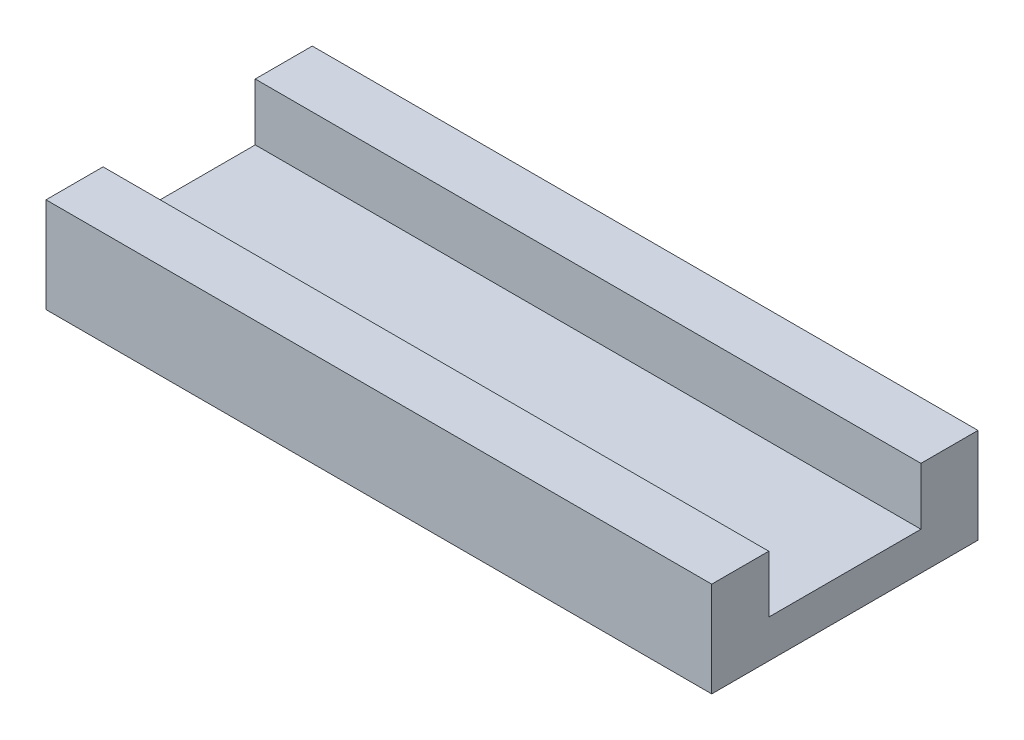
SolidWorks part; units mm, degrees
ref_plane "Front Plane" through (0, 0, 0) normal (0, 0, 1) x (1, 0, 0)
ref_plane "Top Plane" through (0, 0, 0) normal (0, 1, 0) x (1, 0, 0)
ref_plane "Right Plane" through (0, 0, 0) normal (1, 0, 0) x (0, 0, -1)
sketch "Sketch1" plane through (0, 0, 0) normal (1, 0, 0) x (0, 0, -1)
  line L0 (-7, 1) -> (-7, 4)
  line L1 (-7, -1) -> (7, -1)
  line L2 (-7, -1) -> (-7, 1)
  line L3 (-4, 1) -> (4, 1)
  line L4 (7, -1) -> (7, 1)
  line L5 (-7, -1) -> (7, 1) construction
  line L6 (-7, 1) -> (7, -1) construction
  line L7 (-7, 4) -> (-4, 4)
  line L8 (-4, 4) -> (-4, 1)
  line L9 (7, 1) -> (7, 4)
  line L10 (7, 4) -> (4, 4)
  line L11 (4, 4) -> (4, 1)
  point P0 (0, 0)
  point P12 (0, 1)
  point P13 (-4, 1.3048)
  point P14 (0, 0)
  point P15 (-7, 2.3631)
  dimension "D1" = 2
  dimension "D2" = 8
  dimension "D3" = 3
  dimension "D4" = 3
extrude "Boss-Extrude1" add sketch "Sketch1" against normal blind 35
